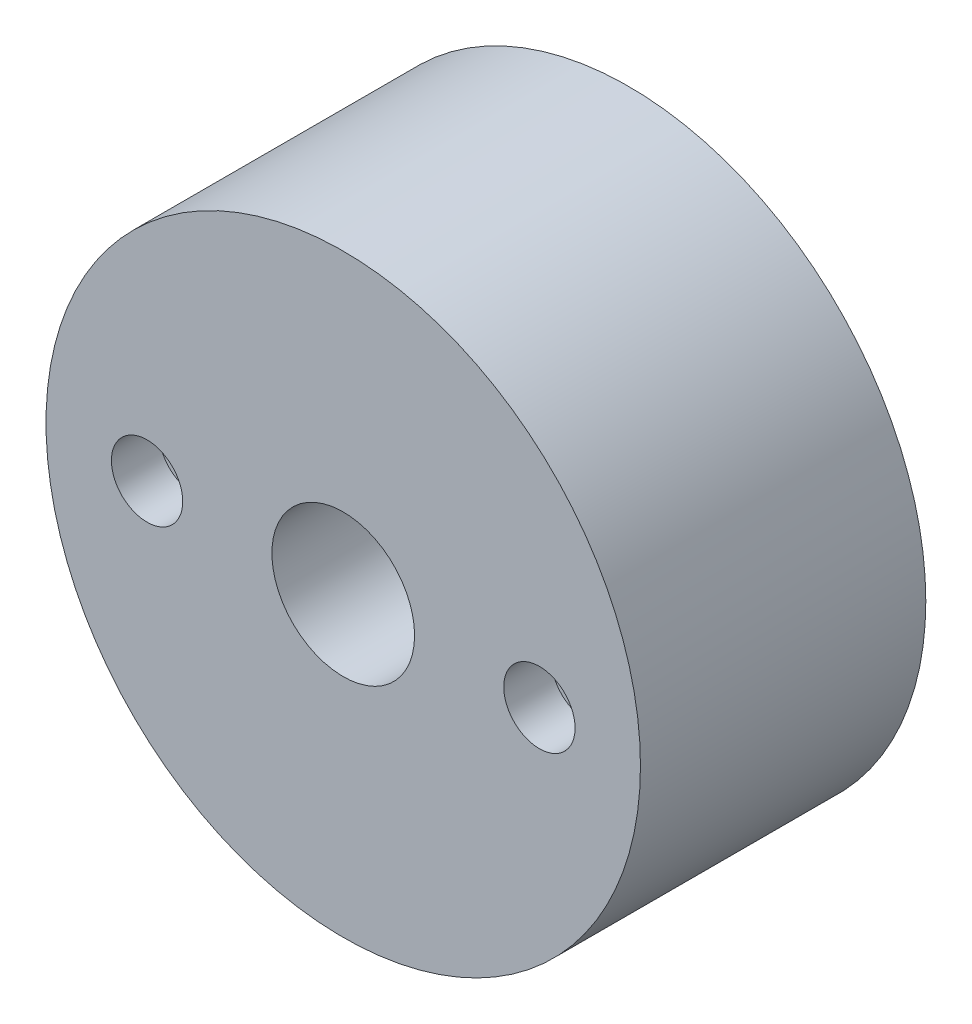
SolidWorks part; units mm, degrees
material "Acier allié inoxydable"
ref_plane "Plan de face" through (0, 0, 0) normal (0, 0, 1) x (1, 0, 0)
ref_plane "Plan de dessus" through (0, 0, 0) normal (0, 1, 0) x (1, 0, 0)
ref_plane "Plan de droite" through (0, 0, 0) normal (1, 0, 0) x (0, 0, -1)
sketch "Esquisse1" plane through (0, 0, 0) normal (0, 0, 1) x (1, 0, 0)
  circle A0 centre (0, 0) radius 12.5
  dimension "D1" = 25
extrude "Boss.-Extru.1" add sketch "Esquisse1" along normal blind 12
sketch "Esquisse2" plane through (0, 0, 12) normal (0, 0, 1) x (1, 0, 0)
  circle A0 centre (0, 0) radius 3
  dimension "D1" = 6
extrude "Enlèv. mat.-Extru.1" cut sketch "Esquisse2" against normal blind 12
sketch "Esquisse3" plane through (0, 0, 12) normal (0, 0, 1) x (1, 0, 0)
  circle A0 centre (-8.25, 0) radius 1.5
  circle A1 centre (8.25, 0) radius 1.5
  dimension "D1" = 3
  dimension "D2" = 16.5
  dimension "D3" = 8.25
extrude "Enlèv. mat.-Extru.2" cut sketch "Esquisse3" against normal blind 2
equation "\"¸6.75\"=6.75"
